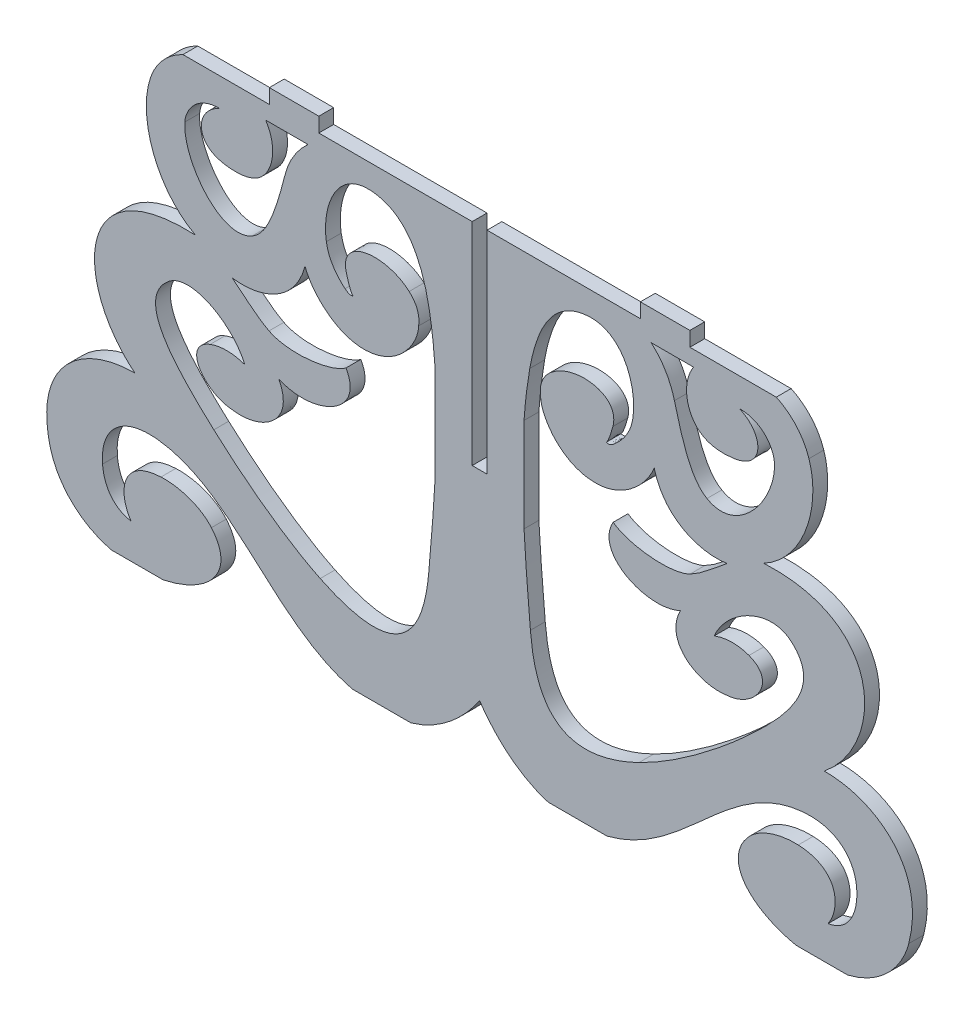
SolidWorks part; units mm, degrees
ref_plane "Plano frontal" through (0, 0, 0) normal (0, 0, 1) x (1, 0, 0)
ref_plane "Plano superior" through (0, 0, 0) normal (0, 1, 0) x (1, 0, 0)
ref_plane "Plano direito" through (0, 0, 0) normal (1, 0, 0) x (0, 0, -1)
sketch "Model" plane through (0, 0, 0) normal (0, 0, 1) x (1, 0, 0)
  line L0 (39.01, -72.758) -> (45.9466, -72.758)
  line L1 (36.3446, -10.1245) -> (24.701, -10.1245)
  line L2 (24.701, -10.1245) -> (24.701, -8.1567)
  line L3 (24.701, -8.1567) -> (18.0344, -8.1567)
  line L4 (18.0344, -8.1567) -> (18.0344, -10.1245)
  line L5 (18.0344, -10.1245) -> (-2.6323, -10.1245)
  line L6 (-2.6323, -10.1245) -> (-2.6323, -38.5956)
  line L7 (-2.6323, -38.5956) -> (-4.6323, -38.5956)
  line L8 (-4.6323, -38.5956) -> (-4.6323, -10.1245)
  line L9 (-4.6323, -10.1245) -> (-25.299, -10.1245)
  line L10 (-25.299, -10.1245) -> (-25.299, -8.1567)
  line L11 (-25.299, -8.1567) -> (-31.9656, -8.1567)
  line L12 (-31.9656, -8.1567) -> (-31.9656, -10.1245)
  line L13 (-31.9656, -10.1245) -> (-43.6092, -10.1245)
  line L14 (-53.2112, -72.758) -> (-46.2746, -72.758)
  line L15 (-20.7922, -72.758) -> (-12.8827, -72.758)
  line L16 (5.6181, -72.758) -> (13.5276, -72.758)
  line L17 (-26.7511, -12.1942) -> (-32.4569, -12.1942)
  line L18 (-9.6217, -42.4913) -> (-9.6217, -29.8374)
  line L19 (19.4865, -12.1942) -> (25.1923, -12.1942)
  line L20 (2.3571, -42.4913) -> (2.3571, -29.8374)
  spline S0 degree 3 poles (13.5276, -72.758) (24.0999, -70.0782) (29.5908, -57.7851) (39.7847, -56.7452) knots 0 0 0 0 0.02381 0.02381 0.02381 0.02381
  spline S1 degree 3 poles (39.7847, -56.7452) (44.8462, -56.229) (47.5126, -59.2874) (47.1792, -63.3321) knots 0.02381 0.02381 0.02381 0.02381 0.047619 0.047619 0.047619 0.047619
  spline S2 degree 3 poles (47.1792, -63.3321) (46.9993, -65.5144) (45.898, -67.632) (43.3255, -68.072) knots 0.047619 0.047619 0.047619 0.047619 0.071429 0.071429 0.071429 0.071429
  spline S3 degree 3 poles (43.3255, -68.072) (45.091, -65.4896) (44.7729, -61.1589) (39.3053, -60.9035) knots 0.071429 0.071429 0.071429 0.071429 0.095238 0.095238 0.095238 0.095238
  spline S4 degree 3 poles (39.3053, -60.9035) (36.7984, -60.7864) (33.9868, -61.6884) (32.5083, -63.4191) knots 0.095238 0.095238 0.095238 0.095238 0.119048 0.119048 0.119048 0.119048
  spline S5 degree 3 poles (32.5083, -63.4191) (29.0675, -67.4468) (32.9753, -71.5011) (39.01, -72.758) knots 0.119048 0.119048 0.119048 0.119048 0.142857 0.142857 0.142857 0.142857
  spline S6 degree 3 poles (45.9466, -72.758) (50.593, -71.6353) (53.3599, -68.2207) (54.1991, -64.9676) knots 0.166667 0.166667 0.166667 0.166667 0.190476 0.190476 0.190476 0.190476
  spline S7 degree 3 poles (54.1991, -64.9676) (56.5947, -55.6799) (50.0219, -50.4817) (42.8047, -50.5322) knots 0.190476 0.190476 0.190476 0.190476 0.214286 0.214286 0.214286 0.214286
  spline S8 degree 3 poles (42.8047, -50.5322) (51.071, -43.9022) (51.1176, -29.5576) (34.6597, -30.3526) knots 0.214286 0.214286 0.214286 0.214286 0.238095 0.238095 0.238095 0.238095
  spline S9 degree 3 poles (34.6597, -30.3526) (39.9859, -27.4897) (42.4387, -20.2826) (40.748, -15.0992) knots 0.238095 0.238095 0.238095 0.238095 0.261905 0.261905 0.261905 0.261905
  spline S10 degree 3 poles (40.748, -15.0992) (40.1089, -13.1398) (38.6749, -11.2333) (36.3446, -10.1245) knots 0.261905 0.261905 0.261905 0.261905 0.285714 0.285714 0.285714 0.285714
  spline S11 degree 3 poles (-43.6092, -10.1245) (-45.9395, -11.2333) (-47.3735, -13.1398) (-48.0126, -15.0992) knots 0.595238 0.595238 0.595238 0.595238 0.619048 0.619048 0.619048 0.619048
  spline S12 degree 3 poles (-48.0126, -15.0992) (-49.7033, -20.2826) (-47.2505, -27.4897) (-41.9243, -30.3526) knots 0.619048 0.619048 0.619048 0.619048 0.642857 0.642857 0.642857 0.642857
  spline S13 degree 3 poles (-41.9243, -30.3526) (-58.3822, -29.5576) (-58.3356, -43.9022) (-50.0693, -50.5322) knots 0.642857 0.642857 0.642857 0.642857 0.666667 0.666667 0.666667 0.666667
  spline S14 degree 3 poles (-50.0693, -50.5322) (-57.2865, -50.4817) (-63.8593, -55.6799) (-61.4637, -64.9676) knots 0.666667 0.666667 0.666667 0.666667 0.690476 0.690476 0.690476 0.690476
  spline S15 degree 3 poles (-61.4637, -64.9676) (-60.6245, -68.2207) (-57.8576, -71.6353) (-53.2112, -72.758) knots 0.690476 0.690476 0.690476 0.690476 0.714286 0.714286 0.714286 0.714286
  spline S16 degree 3 poles (-46.2746, -72.758) (-40.2399, -71.5011) (-36.3321, -67.4468) (-39.7729, -63.4191) knots 0.738095 0.738095 0.738095 0.738095 0.761905 0.761905 0.761905 0.761905
  spline S17 degree 3 poles (-39.7729, -63.4191) (-41.2514, -61.6884) (-44.063, -60.7864) (-46.5699, -60.9035) knots 0.761905 0.761905 0.761905 0.761905 0.785714 0.785714 0.785714 0.785714
  spline S18 degree 3 poles (-46.5699, -60.9035) (-52.0375, -61.1589) (-52.3556, -65.4896) (-50.5901, -68.072) knots 0.785714 0.785714 0.785714 0.785714 0.809524 0.809524 0.809524 0.809524
  spline S19 degree 3 poles (-50.5901, -68.072) (-53.1626, -67.632) (-54.2639, -65.5144) (-54.4438, -63.3321) knots 0.809524 0.809524 0.809524 0.809524 0.833333 0.833333 0.833333 0.833333
  spline S20 degree 3 poles (-54.4438, -63.3321) (-54.7772, -59.2874) (-52.1108, -56.229) (-47.0493, -56.7452) knots 0.833333 0.833333 0.833333 0.833333 0.857143 0.857143 0.857143 0.857143
  spline S21 degree 3 poles (-47.0493, -56.7452) (-36.8554, -57.7851) (-31.3645, -70.0782) (-20.7922, -72.758) knots 0.857143 0.857143 0.857143 0.857143 0.880952 0.880952 0.880952 0.880952
  spline S22 degree 3 poles (-12.8827, -72.758) (-7.3612, -71.1534) (-4.1128, -66.2698) (-3.6323, -65.5117) knots 0.904762 0.904762 0.904762 0.904762 0.928571 0.928571 0.928571 0.928571
  spline S23 degree 3 poles (-3.6323, -65.5117) (-3.1518, -66.2698) (0.0966, -71.1534) (5.6181, -72.758) knots 0.928571 0.928571 0.928571 0.928571 0.952381 0.952381 0.952381 0.952381
  spline S24 degree 3 poles (-32.4569, -12.1942) (-31.1733, -14.1768) (-31.2313, -16.7106) (-32.4844, -18.471) knots 0 0 0 0 0.111111 0.111111 0.111111 0.111111
  spline S25 degree 3 poles (-32.4844, -18.471) (-33.3768, -19.7246) (-35.0403, -20.5546) (-37.9276, -20.132) knots 0.111111 0.111111 0.111111 0.111111 0.222222 0.222222 0.222222 0.222222
  spline S26 degree 3 poles (-37.9276, -20.132) (-42.1519, -19.5136) (-41.9903, -15.4117) (-38.6474, -13.942) knots 0.222222 0.222222 0.222222 0.222222 0.333333 0.333333 0.333333 0.333333
  spline S27 degree 3 poles (-38.6474, -13.942) (-41.6734, -13.9053) (-43.2427, -16.2203) (-43.3562, -17.8679) knots 0.333333 0.333333 0.333333 0.333333 0.444444 0.444444 0.444444 0.444444
  spline S28 degree 3 poles (-43.3562, -17.8679) (-43.6636, -22.3248) (-38.5123, -29.0887) (-34.2704, -26.6235) knots 0.444444 0.444444 0.444444 0.444444 0.555556 0.555556 0.555556 0.555556
  spline S29 degree 3 poles (-34.2704, -26.6235) (-32.5007, -25.5951) (-31.3381, -23.1377) (-29.8837, -17.3969) knots 0.555556 0.555556 0.555556 0.555556 0.666667 0.666667 0.666667 0.666667
  spline S30 degree 3 poles (-29.8837, -17.3969) (-29.3667, -15.3561) (-28.3138, -13.5718) (-26.7511, -12.1942) knots 0.666667 0.666667 0.666667 0.666667 0.777778 0.777778 0.777778 0.777778
  spline S31 degree 3 poles (-9.6217, -29.8374) (-9.7726, -27.6467) (-10.0208, -25.4894) (-10.3939, -23.383) knots 0.041667 0.041667 0.041667 0.041667 0.083333 0.083333 0.083333 0.083333
  spline S32 degree 3 poles (-10.3939, -23.383) (-11.331, -18.092) (-13.5268, -13.6157) (-18.2928, -13.3357) knots 0.083333 0.083333 0.083333 0.083333 0.125 0.125 0.125 0.125
  spline S33 degree 3 poles (-18.2928, -13.3357) (-23.0171, -13.0581) (-24.9083, -18.4091) (-24.2808, -22.2969) knots 0.125 0.125 0.125 0.125 0.166667 0.166667 0.166667 0.166667
  spline S34 degree 3 poles (-24.2808, -22.2969) (-24.0259, -23.8763) (-23.2335, -25.2779) (-21.7588, -26.5225) knots 0.166667 0.166667 0.166667 0.166667 0.208333 0.208333 0.208333 0.208333
  spline S35 degree 3 poles (-21.7588, -26.5225) (-21.3405, -26.8755) (-20.9898, -26.9691) (-20.7021, -26.8374) knots 0.208333 0.208333 0.208333 0.208333 0.25 0.25 0.25 0.25
  spline S36 degree 3 poles (-20.7021, -26.8374) (-20.8973, -26.6785) (-21.1963, -26.0369) (-21.5905, -24.5651) knots 0.25 0.25 0.25 0.25 0.291667 0.291667 0.291667 0.291667
  spline S37 degree 3 poles (-21.5905, -24.5651) (-22.6756, -20.5145) (-16.2984, -19.7002) (-13.1252, -22.5274) knots 0.291667 0.291667 0.291667 0.291667 0.333333 0.333333 0.333333 0.333333
  spline S38 degree 3 poles (-13.1252, -22.5274) (-12.1537, -23.3931) (-11.6464, -24.5495) (-11.8511, -25.9186) knots 0.333333 0.333333 0.333333 0.333333 0.375 0.375 0.375 0.375
  spline S39 degree 3 poles (-11.8511, -25.9186) (-11.9194, -28.4357) (-15.0834, -32.8113) (-20.0254, -32.2725) knots 0.375 0.375 0.375 0.375 0.416667 0.416667 0.416667 0.416667
  spline S40 degree 3 poles (-20.0254, -32.2725) (-23.5148, -31.8921) (-26.3139, -28.9039) (-27.1557, -26.6085) knots 0.416667 0.416667 0.416667 0.416667 0.458333 0.458333 0.458333 0.458333
  spline S41 degree 3 poles (-27.1557, -26.6085) (-28.5683, -31.8996) (-33.5101, -33.4082) (-36.9867, -32.8513) knots 0.458333 0.458333 0.458333 0.458333 0.5 0.5 0.5 0.5
  spline S42 degree 3 poles (-36.9867, -32.8513) (-35.3064, -34.1608) (-33.7715, -35.6527) (-32.007, -36.5689) knots 0.5 0.5 0.5 0.5 0.541667 0.541667 0.541667 0.541667
  spline S43 degree 3 poles (-32.007, -36.5689) (-29.3781, -37.934) (-23.7227, -37.273) (-21.6381, -35.709) knots 0.541667 0.541667 0.541667 0.541667 0.583333 0.583333 0.583333 0.583333
  spline S44 degree 3 poles (-21.6381, -35.709) (-18.9894, -40.335) (-26.1931, -43.6202) (-30.699, -41.5005) knots 0.583333 0.583333 0.583333 0.583333 0.625 0.625 0.625 0.625
  spline S45 degree 3 poles (-30.699, -41.5005) (-28.4119, -45.8308) (-32.9424, -48.9432) (-37.1074, -48.2288) knots 0.625 0.625 0.625 0.625 0.666667 0.666667 0.666667 0.666667
  spline S46 degree 3 poles (-37.1074, -48.2288) (-40.7542, -47.9131) (-43.8613, -43.6198) (-39.9339, -42.1042) knots 0.666667 0.666667 0.666667 0.666667 0.708333 0.708333 0.708333 0.708333
  spline S47 degree 3 poles (-39.9339, -42.1042) (-38.6761, -41.6188) (-36.9586, -41.5293) (-35.2485, -42.1605) knots 0.708333 0.708333 0.708333 0.708333 0.75 0.75 0.75 0.75
  spline S48 degree 3 poles (-35.2485, -42.1605) (-36.9784, -38.1517) (-42.6099, -35.182) (-45.5096, -37.5422) knots 0.75 0.75 0.75 0.75 0.791667 0.791667 0.791667 0.791667
  spline S49 degree 3 poles (-45.5096, -37.5422) (-50.1258, -41.2994) (-44.9673, -46.8017) (-39.4446, -51.8319) knots 0.791667 0.791667 0.791667 0.791667 0.833333 0.833333 0.833333 0.833333
  spline S50 degree 3 poles (-39.4446, -51.8319) (-36.6658, -54.3629) (-30.845, -59.2324) (-25.1107, -62.0186) knots 0.833333 0.833333 0.833333 0.833333 0.875 0.875 0.875 0.875
  spline S51 degree 3 poles (-25.1107, -62.0186) (-13.1524, -67.8289) (-10.9954, -59.9068) (-10.4758, -53.8978) knots 0.875 0.875 0.875 0.875 0.916667 0.916667 0.916667 0.916667
  spline S52 degree 3 poles (-10.4758, -53.8978) (-10.1517, -50.1504) (-9.8219, -46.3199) (-9.6217, -42.4913) knots 0.916667 0.916667 0.916667 0.916667 1 1 1 1
  spline S53 degree 3 poles (25.1923, -12.1942) (23.9087, -14.1768) (23.9667, -16.7106) (25.2198, -18.471) knots 0 0 0 0 0.111111 0.111111 0.111111 0.111111
  spline S54 degree 3 poles (25.2198, -18.471) (26.1122, -19.7246) (27.7757, -20.5546) (30.663, -20.132) knots 0.111111 0.111111 0.111111 0.111111 0.222222 0.222222 0.222222 0.222222
  spline S55 degree 3 poles (30.663, -20.132) (34.8873, -19.5136) (34.7257, -15.4117) (31.3828, -13.942) knots 0.222222 0.222222 0.222222 0.222222 0.333333 0.333333 0.333333 0.333333
  spline S56 degree 3 poles (31.3828, -13.942) (34.4088, -13.9053) (35.9781, -16.2203) (36.0916, -17.8679) knots 0.333333 0.333333 0.333333 0.333333 0.444444 0.444444 0.444444 0.444444
  spline S57 degree 3 poles (36.0916, -17.8679) (36.399, -22.3248) (31.2477, -29.0887) (27.0058, -26.6235) knots 0.444444 0.444444 0.444444 0.444444 0.555556 0.555556 0.555556 0.555556
  spline S58 degree 3 poles (27.0058, -26.6235) (25.2361, -25.5951) (24.0735, -23.1377) (22.6191, -17.3969) knots 0.555556 0.555556 0.555556 0.555556 0.666667 0.666667 0.666667 0.666667
  spline S59 degree 3 poles (22.6191, -17.3969) (22.1021, -15.3561) (21.0492, -13.5718) (19.4865, -12.1942) knots 0.666667 0.666667 0.666667 0.666667 0.777778 0.777778 0.777778 0.777778
  spline S60 degree 3 poles (2.3571, -29.8374) (2.508, -27.6467) (2.7562, -25.4894) (3.1293, -23.383) knots 0.041667 0.041667 0.041667 0.041667 0.083333 0.083333 0.083333 0.083333
  spline S61 degree 3 poles (3.1293, -23.383) (4.0664, -18.092) (6.2622, -13.6157) (11.0282, -13.3357) knots 0.083333 0.083333 0.083333 0.083333 0.125 0.125 0.125 0.125
  spline S62 degree 3 poles (11.0282, -13.3357) (15.7525, -13.0581) (17.6437, -18.4091) (17.0162, -22.2969) knots 0.125 0.125 0.125 0.125 0.166667 0.166667 0.166667 0.166667
  spline S63 degree 3 poles (17.0162, -22.2969) (16.7613, -23.8763) (15.9689, -25.2779) (14.4942, -26.5225) knots 0.166667 0.166667 0.166667 0.166667 0.208333 0.208333 0.208333 0.208333
  spline S64 degree 3 poles (14.4942, -26.5225) (14.0759, -26.8755) (13.7252, -26.9691) (13.4375, -26.8374) knots 0.208333 0.208333 0.208333 0.208333 0.25 0.25 0.25 0.25
  spline S65 degree 3 poles (13.4375, -26.8374) (13.6327, -26.6785) (13.9317, -26.0369) (14.3259, -24.5651) knots 0.25 0.25 0.25 0.25 0.291667 0.291667 0.291667 0.291667
  spline S66 degree 3 poles (14.3259, -24.5651) (15.411, -20.5145) (9.0338, -19.7002) (5.8606, -22.5274) knots 0.291667 0.291667 0.291667 0.291667 0.333333 0.333333 0.333333 0.333333
  spline S67 degree 3 poles (5.8606, -22.5274) (4.8891, -23.3931) (4.3818, -24.5495) (4.5865, -25.9186) knots 0.333333 0.333333 0.333333 0.333333 0.375 0.375 0.375 0.375
  spline S68 degree 3 poles (4.5865, -25.9186) (4.6548, -28.4357) (7.8188, -32.8113) (12.7608, -32.2725) knots 0.375 0.375 0.375 0.375 0.416667 0.416667 0.416667 0.416667
  spline S69 degree 3 poles (12.7608, -32.2725) (16.2502, -31.8921) (19.0493, -28.9039) (19.8911, -26.6085) knots 0.416667 0.416667 0.416667 0.416667 0.458333 0.458333 0.458333 0.458333
  spline S70 degree 3 poles (19.8911, -26.6085) (21.3037, -31.8996) (26.2455, -33.4082) (29.7221, -32.8513) knots 0.458333 0.458333 0.458333 0.458333 0.5 0.5 0.5 0.5
  spline S71 degree 3 poles (29.7221, -32.8513) (28.0418, -34.1608) (26.5069, -35.6527) (24.7424, -36.5689) knots 0.5 0.5 0.5 0.5 0.541667 0.541667 0.541667 0.541667
  spline S72 degree 3 poles (24.7424, -36.5689) (22.1135, -37.934) (16.4581, -37.273) (14.3735, -35.709) knots 0.541667 0.541667 0.541667 0.541667 0.583333 0.583333 0.583333 0.583333
  spline S73 degree 3 poles (14.3735, -35.709) (11.7248, -40.335) (18.9285, -43.6202) (23.4344, -41.5005) knots 0.583333 0.583333 0.583333 0.583333 0.625 0.625 0.625 0.625
  spline S74 degree 3 poles (23.4344, -41.5005) (21.1473, -45.8308) (25.6778, -48.9432) (29.8428, -48.2288) knots 0.625 0.625 0.625 0.625 0.666667 0.666667 0.666667 0.666667
  spline S75 degree 3 poles (29.8428, -48.2288) (33.4896, -47.9131) (36.5967, -43.6198) (32.6693, -42.1042) knots 0.666667 0.666667 0.666667 0.666667 0.708333 0.708333 0.708333 0.708333
  spline S76 degree 3 poles (32.6693, -42.1042) (31.4115, -41.6188) (29.694, -41.5293) (27.9839, -42.1605) knots 0.708333 0.708333 0.708333 0.708333 0.75 0.75 0.75 0.75
  spline S77 degree 3 poles (27.9839, -42.1605) (29.7138, -38.1517) (35.3453, -35.182) (38.245, -37.5422) knots 0.75 0.75 0.75 0.75 0.791667 0.791667 0.791667 0.791667
  spline S78 degree 3 poles (38.245, -37.5422) (42.8612, -41.2994) (37.7027, -46.8017) (32.18, -51.8319) knots 0.791667 0.791667 0.791667 0.791667 0.833333 0.833333 0.833333 0.833333
  spline S79 degree 3 poles (32.18, -51.8319) (29.4012, -54.3629) (23.5804, -59.2324) (17.8461, -62.0186) knots 0.833333 0.833333 0.833333 0.833333 0.875 0.875 0.875 0.875
  spline S80 degree 3 poles (17.8461, -62.0186) (5.8878, -67.8289) (3.7308, -59.9068) (3.2112, -53.8978) knots 0.875 0.875 0.875 0.875 0.916667 0.916667 0.916667 0.916667
  spline S81 degree 3 poles (3.2112, -53.8978) (2.8871, -50.1504) (2.5573, -46.3199) (2.3571, -42.4913) knots 0.916667 0.916667 0.916667 0.916667 1 1 1 1
extrude "Ressalto-extrusão1" add sketch "Model" along normal blind 2
